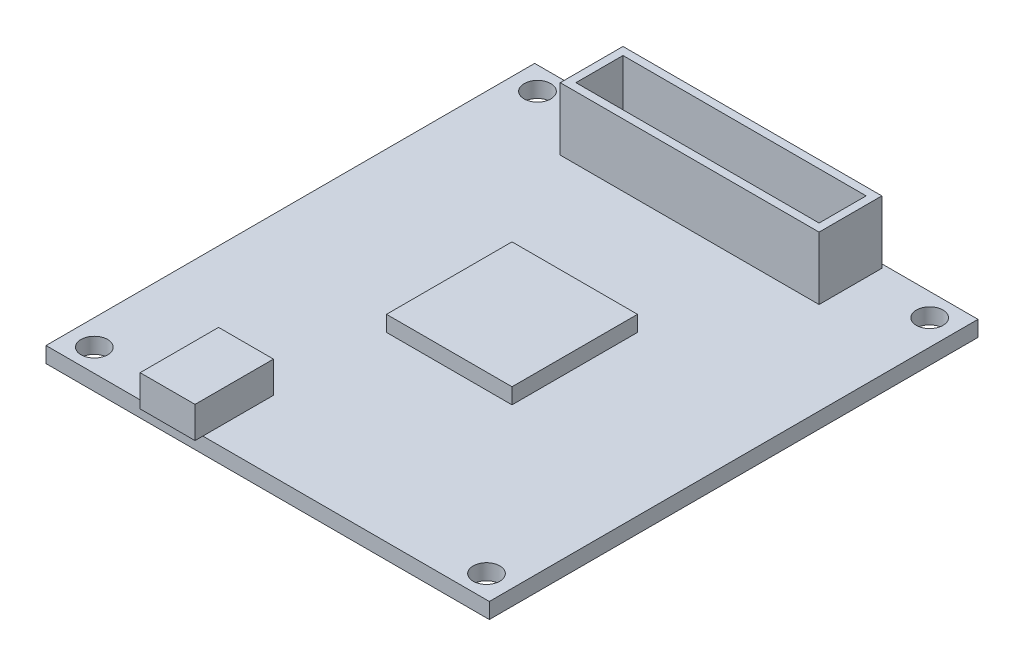
SolidWorks part; units mm, degrees
ref_plane "前视基准面" through (0, 0, 0) normal (0, 0, 1) x (1, 0, 0)
ref_plane "上视基准面" through (0, 0, 0) normal (0, 1, 0) x (1, 0, 0)
ref_plane "右视基准面" through (0, 0, 0) normal (1, 0, 0) x (0, 0, -1)
sketch "草图1" plane through (0, 0, 0) normal (0, 1, 0) x (1, 0, 0)
  line L0 (0, 0) -> (0, 31.0959) construction
  line L1 (-28.26, -31.15) -> (28.26, -31.15)
  line L2 (-28.26, -31.15) -> (-28.26, 31.15)
  line L3 (-28.26, 31.15) -> (28.26, 31.15)
  line L4 (28.26, -31.15) -> (28.26, 31.15)
  line L5 (-28.26, -31.15) -> (28.26, 31.15) construction
  line L6 (-28.26, 31.15) -> (28.26, -31.15) construction
  line L7 (0, 0) -> (42.5477, 0) construction
  circle A0 centre (25, 28.25) radius 1.7
  circle A1 centre (25, -28.25) radius 1.7
  circle A2 centre (-25, -28.25) radius 1.7
  circle A3 centre (-25, 28.25) radius 1.7
  point P0 (0, 0)
  dimension "D3" = 50
  dimension "D4" = 56.5
  dimension "D5" = 3.4
  dimension "D1" = 62.3
  dimension "D2" = 56.52
extrude "凸台-拉伸1" add sketch "草图1" along normal blind 2
sketch "草图2" plane through (0, 2, 0) normal (0, 1, 0) x (1, 0, 0)
  line L1 (-8, 8) -> (8, 8)
  line L2 (-8, 8) -> (-8, -8)
  line L3 (-8, -8) -> (8, -8)
  line L4 (8, 8) -> (8, -8)
  line L5 (-8, 8) -> (8, -8) construction
  line L6 (-8, -8) -> (8, 8) construction
  point P0 (0, 0)
  dimension "D1" = 16
  dimension "D2" = 16
extrude "凸台-拉伸2" add sketch "草图2" along normal blind 2
sketch "草图3" plane through (0, 2, 0) normal (0, 1, 0) x (1, 0, 0)
  line L0 (28.26, 31.15) -> (-28.26, 31.15) construction
  line L1 (16.5, 30.65) -> (-16.5, 30.65)
  line L2 (16.5, 30.65) -> (16.5, 22.65)
  line L3 (16.5, 22.65) -> (-16.5, 22.65)
  line L4 (-16.5, 30.65) -> (-16.5, 22.65)
  line L5 (16.5, 30.65) -> (-16.5, 22.65) construction
  line L6 (16.5, 22.65) -> (-16.5, 30.65) construction
  point P0 (0, 26.65)
  point P8 (0, 31.15)
  dimension "D1" = 33
  dimension "D2" = 8
  dimension "D3" = 0.5
extrude "凸台-拉伸3" add sketch "草图3" along normal blind 8
sketch "草图4" plane through (0, 10, 0) normal (0, 1, 0) x (1, 0, 0)
  line L8 (-15.5, 29.65) -> (-15.5, 23.65)
  line L9 (-15.5, 23.65) -> (15.5, 23.65)
  line L10 (15.5, 23.65) -> (15.5, 29.65)
  line L11 (15.5, 29.65) -> (-15.5, 29.65)
  line L12 (-15.5, 29.65) -> (-15.5, 23.65)
  line L13 (-15.5, 23.65) -> (15.5, 23.65)
  line L14 (15.5, 23.65) -> (15.5, 29.65)
  line L15 (15.5, 29.65) -> (-15.5, 29.65)
  dimension "D1" = 1
extrude "切除-拉伸1" cut sketch "草图4" against normal blind 8
sketch "草图5" plane through (0, 2, 0) normal (0, 1, 0) x (1, 0, 0)
  line L0 (-28.26, 31.15) -> (-28.26, -31.15) construction
  line L1 (-8.26, -22.15) -> (-15.26, -22.15)
  line L2 (-8.26, -22.15) -> (-8.26, -32.15)
  line L3 (-8.26, -32.15) -> (-15.26, -32.15)
  line L4 (-15.26, -22.15) -> (-15.26, -32.15)
  line L5 (-8.26, -22.15) -> (-15.26, -32.15) construction
  line L6 (-8.26, -32.15) -> (-15.26, -22.15) construction
  line L8 (-28.26, -31.15) -> (28.26, -31.15) construction
  point P0 (-11.76, -27.15)
  point P7 (-11.76, -28.122)
  dimension "D1" = 10
  dimension "D2" = 7
  dimension "D3" = 13
  dimension "D4" = 1
extrude "凸台-拉伸4" add sketch "草图5" along normal blind 4
